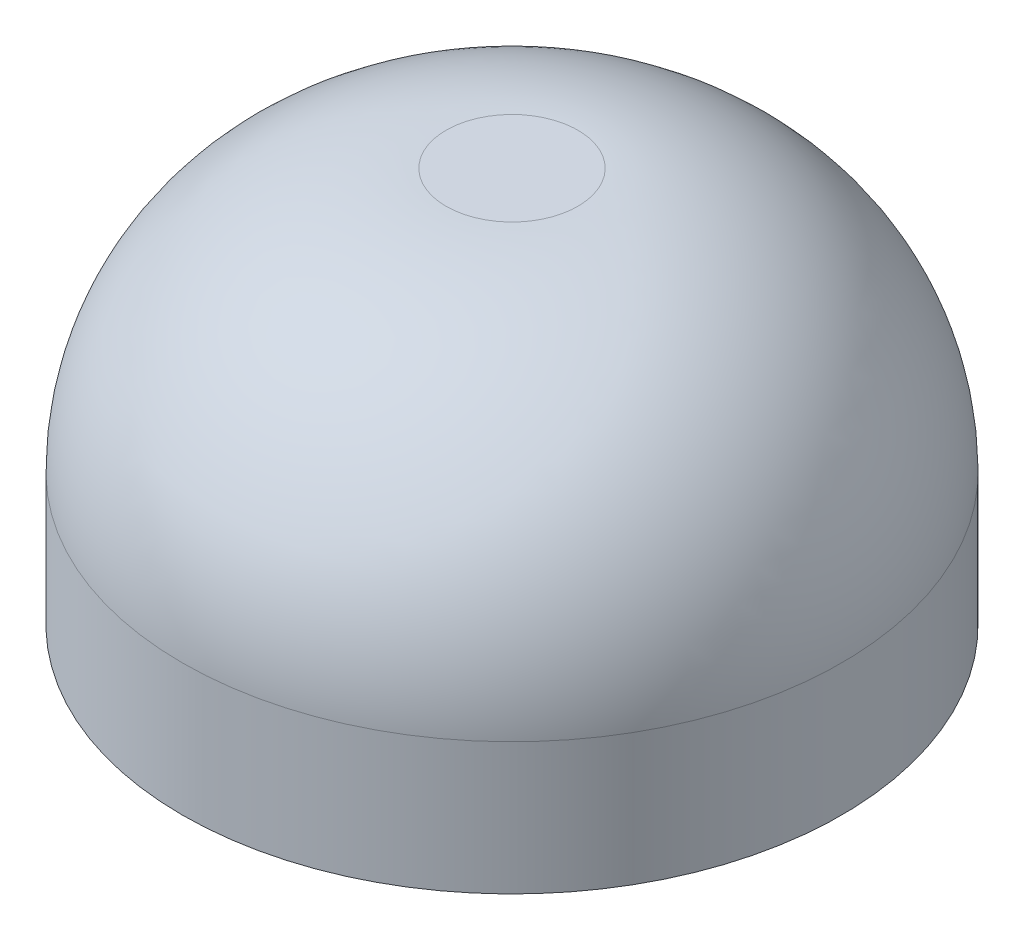
SolidWorks part; units mm, degrees
ref_plane "Front" through (0, 0, 0) normal (0, 0, 1) x (1, 0, 0)
ref_plane "Top" through (0, 0, 0) normal (0, 1, 0) x (1, 0, 0)
ref_plane "Right" through (0, 0, 0) normal (1, 0, 0) x (0, 0, -1)
sketch "Sketch1" plane through (0, 0, 0) normal (0, 1, 0) x (1, 0, 0)
  circle A0 centre (0, 0) radius 2.5
  dimension "D1" = 5
extrude "Boss-Extrude1" add sketch "Sketch1" along normal blind 3 contours A0
sketch "Sketch3" plane through (0, 0, 0) normal (0, 1, 0) x (1, 0, 0)
  circle A0 centre (0, 0) radius 0.5
  dimension "D1" = 1
extrude "Cut-Extrude1" cut sketch "Sketch3" along normal blind 1.5
fillet "Fillet1" radius 2 1 edges at (0, 3, 2.5)
